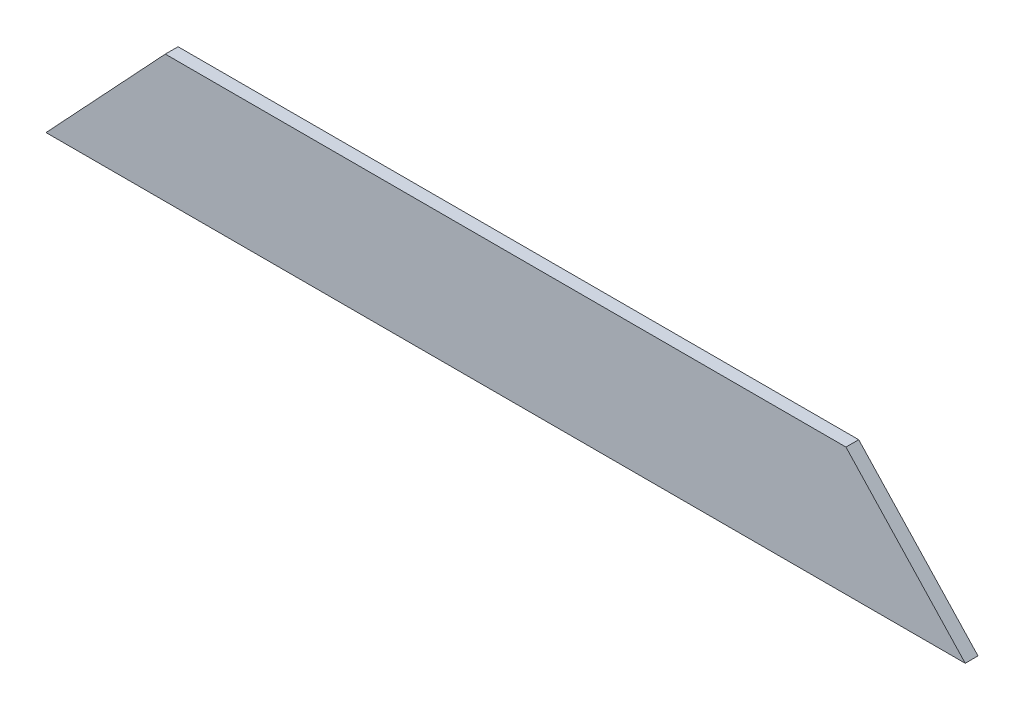
SolidWorks part; units mm, degrees
ref_plane "Front Plane" through (0, 0, 0) normal (0, 0, 1) x (1, 0, 0)
ref_plane "Top Plane" through (0, 0, 0) normal (0, 1, 0) x (1, 0, 0)
ref_plane "Right Plane" through (0, 0, 0) normal (1, 0, 0) x (0, 0, -1)
sketch "Sketch1" plane through (0, 0, 0) normal (0, 0, 1) x (1, 0, 0)
  line L0 (47.6465, 64.9189) -> (154.3149, 64.9189)
  line L1 (100.9807, 121.9741) -> (-114.0193, -108.0259) construction
  line L2 (100.9807, 121.9741) -> (315.9807, -108.0259) construction
  line L3 (154.3149, 64.9189) -> (173.0106, 44.9189)
  line L4 (173.0106, 44.9189) -> (28.9509, 44.9189)
  line L5 (28.9509, 44.9189) -> (47.6465, 64.9189)
  dimension "D1" = 20
extrude "Boss-Extrude1" add sketch "Sketch1" along normal blind 2
